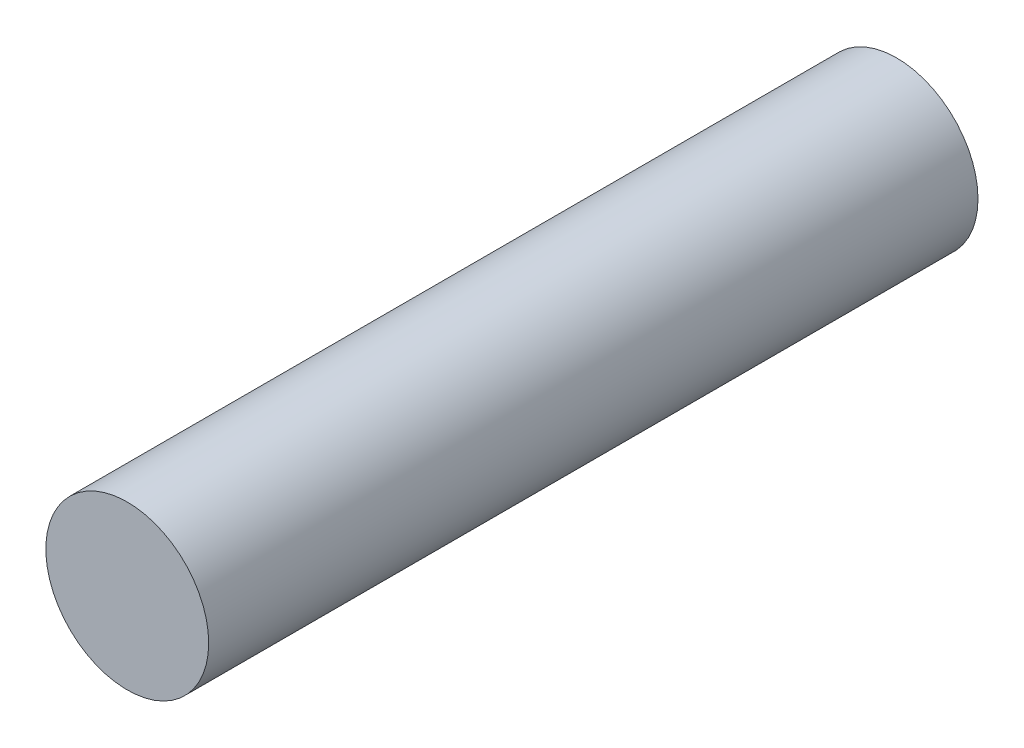
SolidWorks part; units mm, degrees
ref_plane "Front Plane" through (0, 0, 0) normal (0, 0, 1) x (1, 0, 0)
ref_plane "Top Plane" through (0, 0, 0) normal (0, 1, 0) x (1, 0, 0)
ref_plane "Right Plane" through (0, 0, 0) normal (1, 0, 0) x (0, 0, -1)
sketch "Sketch1" plane through (0, 0, 0) normal (0, 0, 1) x (1, 0, 0)
  circle A0 centre (0, 0) radius 50.8
  dimension "D1" = 101.6
extrude "Boss-Extrude1" add sketch "Sketch1" along normal blind 187 and the other way blind 293
